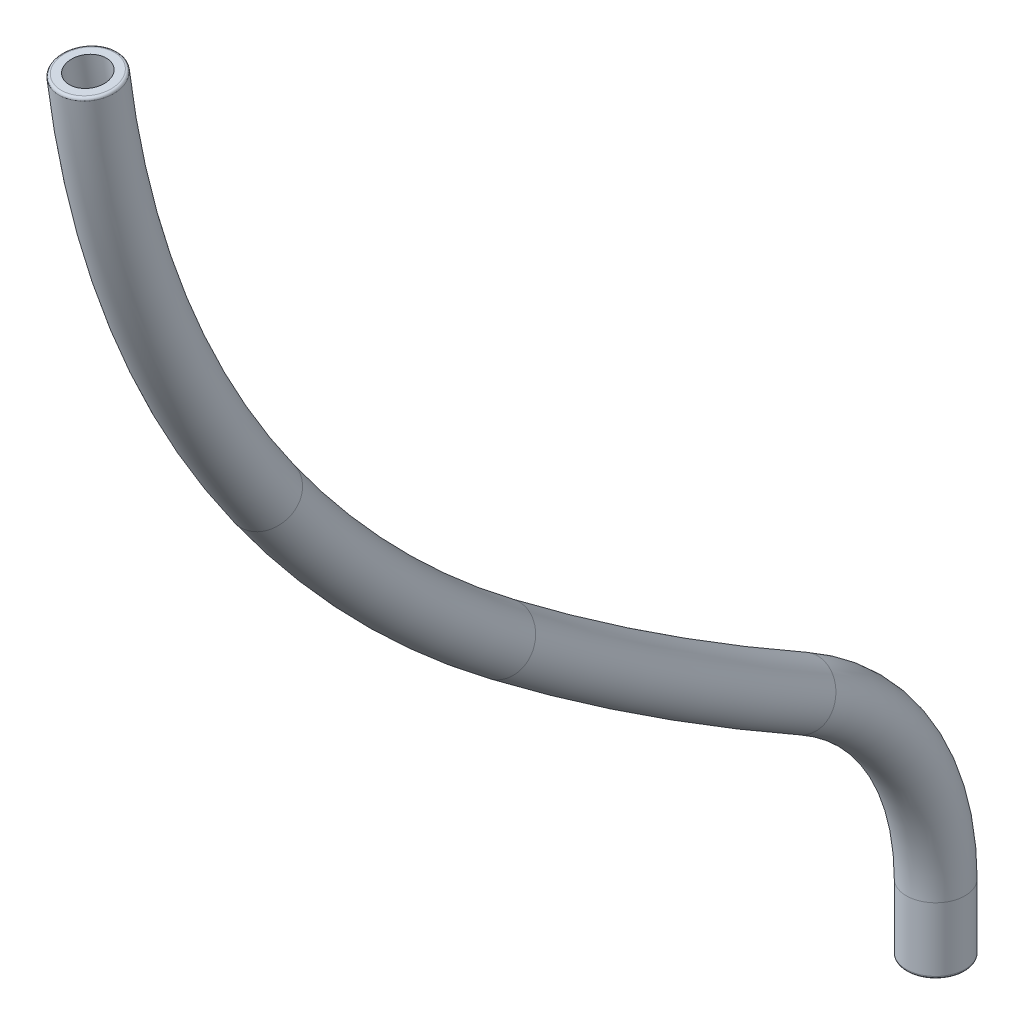
SolidWorks part; units mm, degrees
ref_plane "Alzado" through (0, 0, 0) normal (0, 0, 1) x (1, 0, 0)
ref_plane "Planta" through (0, 0, 0) normal (0, 1, 0) x (1, 0, 0)
ref_plane "Vista lateral" through (0, 0, 0) normal (1, 0, 0) x (0, 0, -1)
sketch "Croquis10" plane through (0, 0, 0) normal (-1, 0, 0) x (0, 0, -1)
  line L0 (0, 0) -> (0, -24.9109)
  arc A0 (0, -24.9109) -> (-49.6907, -109.98) centre (-97.6634, -24.9109) cw
  arc A1 (-49.6907, -109.98) -> (-162.9703, -184.3695) centre (443.1227, -983.8765) ccw
  arc A2 (-162.9703, -184.3695) -> (-251.7582, -275.7801) centre (92.417, -521.255) ccw
  arc A3 (-251.7582, -275.7801) -> (-318.1725, -446.4396) centre (51.4307, -492.0225) ccw
ref_plane "Plano2" through (0, 0, 0) normal (0, 1, 0) x (-1, 0, 0)
sketch "Croquis11" plane through (0, 0, 0) normal (0, 1, 0) x (-1, 0, 0)
  circle A0 centre (0, 0) radius 11
  dimension "D1" = 22
sweep "Barrer4" add profiles "Croquis11" path "Croquis10"
shell "Vaciado5" thickness 4
fillet "Redondeo3" radius 1 2 edges at (-11, 446.4396, 318.1725) (-11, 0, 0)
